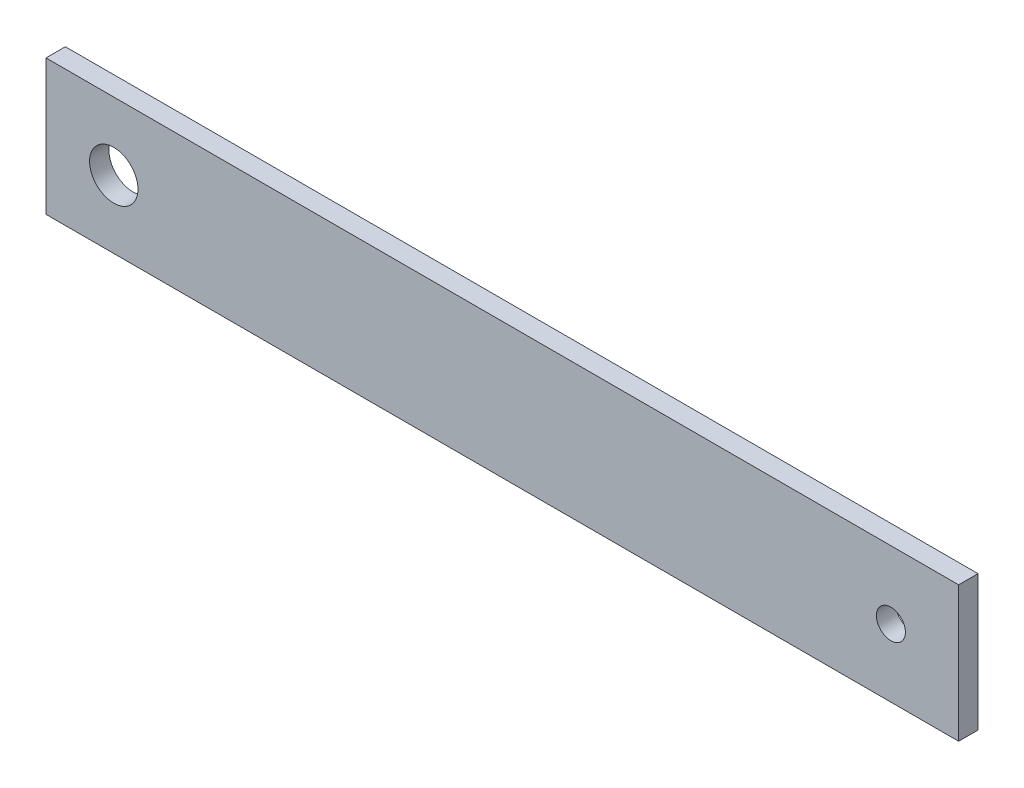
SolidWorks part; units mm, degrees
ref_plane "前视基准面" through (0, 0, 0) normal (0, 0, 1) x (1, 0, 0)
ref_plane "上视基准面" through (0, 0, 0) normal (0, 1, 0) x (1, 0, 0)
ref_plane "右视基准面" through (0, 0, 0) normal (1, 0, 0) x (0, 0, -1)
other "Configuration Table"
sketch "草图1" plane through (0, 0, 0) normal (0, 0, 1) x (1, 0, 0)
  line L1 (-14, -14) -> (174.6, -14)
  line L2 (-14, -14) -> (-14, 14)
  line L3 (-14, 14) -> (174.6, 14)
  line L4 (174.6, -14) -> (174.6, 14)
  line L5 (-14, -14) -> (174.6, 14) construction
  line L6 (-14, 14) -> (174.6, -14) construction
  circle A0 centre (0, 0) radius 5
  circle A1 centre (160.6, 0) radius 3
  point P0 (80.3, 0)
extrude "凸台-拉伸1" add sketch "草图1" along normal mid plane 4
